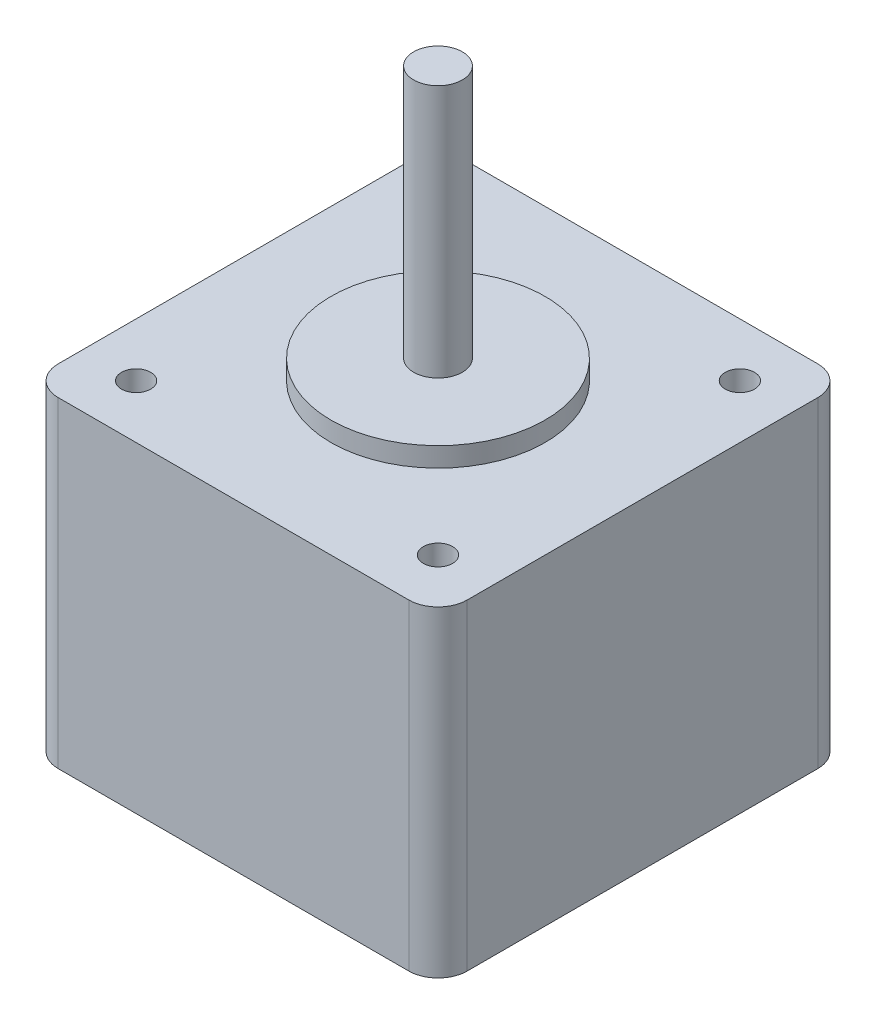
SolidWorks part; units mm, degrees
ref_plane "Front Plane" through (0, 0, 0) normal (0, 0, 1) x (1, 0, 0)
ref_plane "Top Plane" through (0, 0, 0) normal (0, 1, 0) x (1, 0, 0)
ref_plane "Right Plane" through (0, 0, 0) normal (1, 0, 0) x (0, 0, -1)
sketch "Sketch1" plane through (0, 0, 0) normal (0, 1, 0) x (1, 0, 0)
  line L0 (0, 42) -> (0, 0)
  line L1 (0, 0) -> (42, 0)
  line L2 (42, 0) -> (42, 42)
  line L3 (42, 42) -> (0, 42)
  dimension "D1" = 42
  dimension "D2" = 42
extrude "Boss-Extrude1" add sketch "Sketch1" along normal blind 33
sketch "Sketch2" plane through (0, 33, 0) normal (0, 1, 0) x (1, 0, 0)
  line L0 (0, 42) -> (42, 0) construction
  line L1 (0, 0) -> (42, 42) construction
  circle A1 centre (21, 21) radius 2.5
  dimension "D1" = 5
extrude "Boss-Extrude2" add sketch "Sketch2" along normal blind 28
fillet "Fillet1" radius 3 4 edges at (42, 16.5, -42) (42, 16.5, 0) (0, 16.5, 0) (0, 16.5, -42)
ref_plane "Plane1" through (0, 33, 0) normal (0, 1, 0) x (1, 0, 0)
sketch "Sketch3" plane through (0, 33, 0) normal (0, 1, 0) x (1, 0, 0)
  line L0 (21, 42) -> (21, 0)
  line L1 (39, 42) -> (3, 42) construction
  line L2 (3, 0) -> (39, 0) construction
  line L3 (0, 21) -> (42, 21) construction
  line L4 (0, 39) -> (0, 3) construction
  line L5 (42, 3) -> (42, 39) construction
  circle A0 centre (5.5, 36.5) radius 1.5
  circle A1 centre (5.5, 5.5) radius 1.5
  circle A2 centre (36.5, 5.5) radius 1.5
  circle A3 centre (36.5, 36.5) radius 1.5
  dimension "D1" = 3
  dimension "D2" = 15.5
  dimension "D3" = 15.5
extrude "Cut-Extrude1" cut sketch "Sketch3" against normal blind 4.5 contours A0 | A3 | A1 | A2
sketch "Sketch4" plane through (0, 33, 0) normal (0, 1, 0) x (1, 0, 0)
  circle A1 centre (21, 21) radius 11
  dimension "D1" = 22
extrude "Boss-Extrude3" add sketch "Sketch4" along normal blind 2
